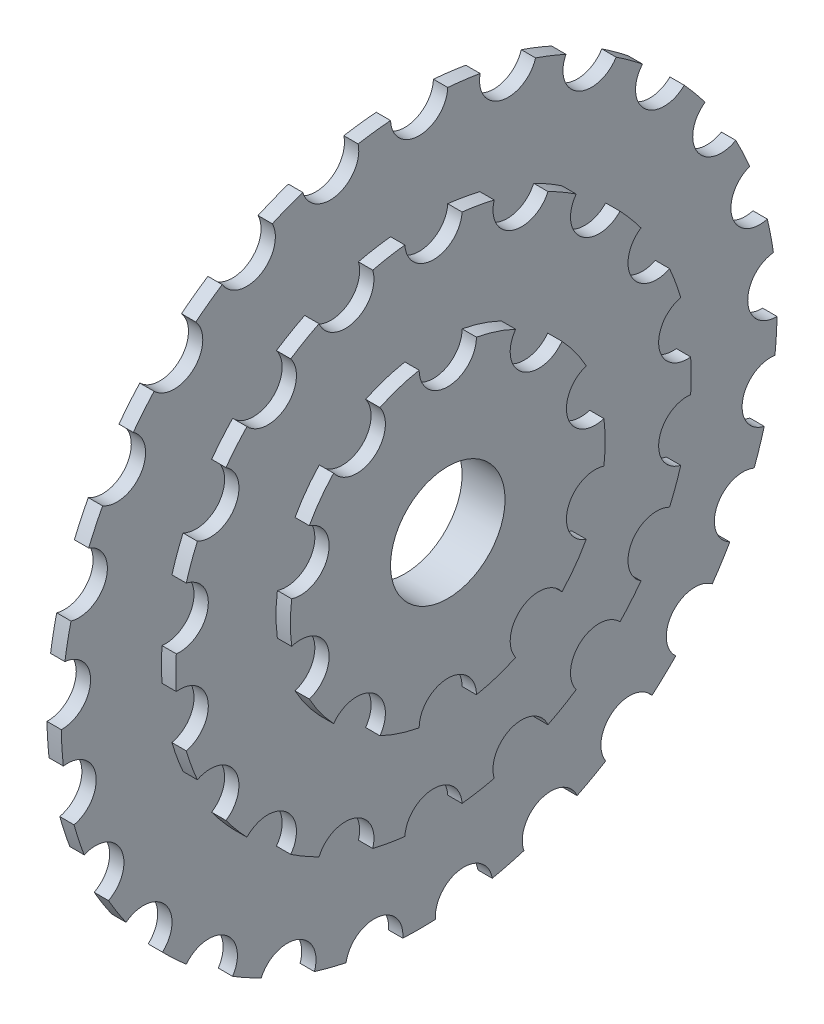
SolidWorks part; units mm, degrees
ref_plane "Front Plane" through (0, 0, 0) normal (0, 0, 1) x (1, 0, 0)
ref_plane "Top Plane" through (0, 0, 0) normal (0, 1, 0) x (1, 0, 0)
ref_plane "Right Plane" through (0, 0, 0) normal (1, 0, 0) x (0, 0, -1)
sketch "Sketch1" plane through (0, 0, 0) normal (1, 0, 0) x (0, 0, -1)
  circle A0 centre (0, 0) radius 338.5
  dimension "D1" = 677
sketch "Sketch2" plane through (0, 0, 0) normal (1, 0, 0) x (0, 0, -1)
  line L0 (-935.3702, 226.3146) -> (-163.5974, 226.3146) construction
sketch "Sketch3" plane through (0, 0, 0) normal (1, 0, 0) x (0, 0, -1)
  line L2 (-1063.2861, 71.897) -> (-1063.2861, -34.0827) construction
  arc A0 (-1068.2821, 62.3) -> (-1073.9404, 61.5852) centre (-1063.2861, 0) ccw
  arc A1 (-1068.2821, 62.3) -> (-1058.2901, 62.3) centre (-1063.2861, 62.5) ccw
  arc A2 (-1052.6317, 61.5852) -> (-1042.9537, 59.1003) centre (-1047.743, 60.5364) ccw
  arc A3 (-1037.6508, 57.0007) -> (-1028.8948, 52.1871) centre (-1033.1765, 54.7692) ccw
  arc A4 (-1024.2807, 48.8347) -> (-1016.9969, 41.9947) centre (-1020.5019, 45.5605) ccw
  arc A5 (-1013.3614, 37.6003) -> (-1008.0075, 29.1637) centre (-1010.5156, 33.4892) ccw
  arc A6 (-1005.5791, 24.0032) -> (-1002.4914, 14.5003) centre (-1003.845, 19.3136) ccw
  arc A7 (-1001.4227, 8.898) -> (-1000.7953, -1.0743) centre (-1000.9094, 3.9244) ccw
  arc A8 (-1001.1534, -6.7664) -> (-1003.0257, -16.5814) centre (-1001.8931, -11.7113) ccw
  arc A9 (-1004.7882, -22.0055) -> (-1009.0425, -31.0466) centre (-1006.7344, -26.6112) ccw
  arc A10 (-1012.0985, -35.862) -> (-1018.4677, -43.561) centre (-1015.129, -39.839) ccw
  arc A11 (-1022.6252, -47.4652) -> (-1030.7089, -53.3383) centre (-1026.5495, -50.5636) ccw
  arc A12 (-1035.7068, -56.0859) -> (-1044.9971, -59.7642) centre (-1040.2783, -58.111) ccw
  arc A13 (-1050.5212, -61.1826) -> (-1060.4344, -62.4349) centre (-1055.4527, -62.0072) ccw
  arc A14 (-1066.1377, -62.4349) -> (-1076.0509, -61.1826) centre (-1071.1194, -62.0072) ccw
  arc A15 (-1081.5751, -59.7642) -> (-1090.8654, -56.0859) centre (-1086.2939, -58.111) ccw
  arc A16 (-1095.8632, -53.3383) -> (-1103.9469, -47.4652) centre (-1100.0227, -50.5636) ccw
  arc A17 (-1108.1045, -43.561) -> (-1114.4736, -35.862) centre (-1111.4432, -39.839) ccw
  arc A18 (-1117.5296, -31.0466) -> (-1121.784, -22.0055) centre (-1119.8378, -26.6112) ccw
  arc A19 (-1123.5464, -16.5814) -> (-1125.4187, -6.7664) centre (-1124.679, -11.7113) ccw
  arc A20 (-1125.7768, -1.0743) -> (-1125.1494, 8.898) centre (-1125.6627, 3.9244) ccw
  arc A21 (-1124.0807, 14.5003) -> (-1120.993, 24.0032) centre (-1122.7271, 19.3136) ccw
  arc A22 (-1118.5647, 29.1637) -> (-1113.2107, 37.6003) centre (-1116.0566, 33.4892) ccw
  arc A23 (-1109.5753, 41.9947) -> (-1102.2914, 48.8347) centre (-1106.0703, 45.5605) ccw
  arc A24 (-1097.6774, 52.1871) -> (-1088.9213, 57.0007) centre (-1093.3957, 54.7692) ccw
  arc A25 (-1083.6185, 59.1003) -> (-1073.9404, 61.5852) centre (-1078.8292, 60.5364) ccw
  arc A26 (-1083.6185, 59.1003) -> (-1088.9213, 57.0007) centre (-1063.2861, 0) ccw
  arc A27 (-1097.6774, 52.1871) -> (-1102.2914, 48.8347) centre (-1063.2861, 0) ccw
  arc A28 (-1109.5753, 41.9947) -> (-1113.2107, 37.6003) centre (-1063.2861, 0) ccw
  arc A29 (-1118.5647, 29.1637) -> (-1120.993, 24.0032) centre (-1063.2861, 0) ccw
  arc A30 (-1124.0807, 14.5003) -> (-1125.1494, 8.898) centre (-1063.2861, 0) ccw
  arc A31 (-1125.7768, -1.0743) -> (-1125.4187, -6.7664) centre (-1063.2861, 0) ccw
  arc A32 (-1123.5464, -16.5814) -> (-1121.784, -22.0055) centre (-1063.2861, 0) ccw
  arc A33 (-1117.5296, -31.0466) -> (-1114.4736, -35.862) centre (-1063.2861, 0) ccw
  arc A34 (-1108.1045, -43.561) -> (-1103.9469, -47.4652) centre (-1063.2861, 0) ccw
  arc A35 (-1095.8632, -53.3383) -> (-1090.8654, -56.0859) centre (-1063.2861, 0) ccw
  arc A36 (-1081.5751, -59.7642) -> (-1076.0509, -61.1826) centre (-1063.2861, 0) ccw
  arc A37 (-1066.1377, -62.4349) -> (-1060.4344, -62.4349) centre (-1063.2861, 0) ccw
  arc A38 (-1050.5212, -61.1826) -> (-1044.9971, -59.7642) centre (-1063.2861, 0) ccw
  arc A39 (-1035.7068, -56.0859) -> (-1030.7089, -53.3383) centre (-1063.2861, 0) ccw
  arc A40 (-1022.6252, -47.4652) -> (-1018.4677, -43.561) centre (-1063.2861, 0) ccw
  arc A41 (-1012.0985, -35.862) -> (-1009.0425, -31.0466) centre (-1063.2861, 0) ccw
  arc A42 (-1004.7882, -22.0055) -> (-1003.0257, -16.5814) centre (-1063.2861, 0) ccw
  arc A43 (-1001.1534, -6.7664) -> (-1000.7953, -1.0743) centre (-1063.2861, 0) ccw
  arc A44 (-1001.4227, 8.898) -> (-1002.4914, 14.5003) centre (-1063.2861, 0) ccw
  arc A45 (-1005.5791, 24.0032) -> (-1008.0075, 29.1637) centre (-1063.2861, 0) ccw
  arc A46 (-1013.3614, 37.6003) -> (-1016.9969, 41.9947) centre (-1063.2861, 0) ccw
  arc A47 (-1024.2807, 48.8347) -> (-1028.8948, 52.1871) centre (-1063.2861, 0) ccw
  arc A48 (-1037.6508, 57.0007) -> (-1042.9537, 59.1003) centre (-1063.2861, 0) ccw
  arc A49 (-1052.6317, 61.5852) -> (-1058.2901, 62.3) centre (-1063.2861, 0) ccw
  point P81 (-1063.2861, 0)
  dimension "D1" = 125
  dimension "D3" = 10
  dimension "D2" = 25
extrude "Boss-Extrude1" add sketch "Sketch3" along normal blind 2.5
sketch "Sketch4" plane through (2.5, 0, 0) normal (1, 0, 0) x (0, 0, -1)
  line L2 (-1063.2861, 49.1439) -> (-1063.2861, -23.1666) construction
  arc A0 (-1068.2784, 44.7222) -> (-1073.8908, 43.7326) centre (-1063.2861, 0) ccw
  arc A1 (-1068.2784, 44.7222) -> (-1058.2938, 44.7222) centre (-1063.2861, 45) ccw
  arc A2 (-1052.6814, 43.7326) -> (-1043.299, 40.3177) centre (-1047.8952, 42.2862) ccw
  arc A3 (-1038.3635, 37.4682) -> (-1030.7149, 31.0502) centre (-1034.3606, 34.472) ccw
  arc A4 (-1027.0516, 26.6846) -> (-1022.0594, 18.0377) centre (-1024.3149, 22.5) ccw
  arc A5 (-1020.1102, 12.6824) -> (-1018.3764, 2.8495) centre (-1018.9697, 7.8142) ccw
  arc A6 (-1018.3764, -2.8495) -> (-1020.1102, -12.6824) centre (-1018.9697, -7.8142) ccw
  arc A7 (-1022.0594, -18.0377) -> (-1027.0516, -26.6846) centre (-1024.3149, -22.5) ccw
  arc A8 (-1030.7149, -31.0502) -> (-1038.3635, -37.4682) centre (-1034.3606, -34.472) ccw
  arc A9 (-1043.299, -40.3177) -> (-1052.6814, -43.7326) centre (-1047.8952, -42.2862) ccw
  arc A10 (-1058.2938, -44.7222) -> (-1068.2784, -44.7222) centre (-1063.2861, -45) ccw
  arc A11 (-1073.8908, -43.7326) -> (-1083.2732, -40.3177) centre (-1078.677, -42.2862) ccw
  arc A12 (-1088.2087, -37.4682) -> (-1095.8573, -31.0502) centre (-1092.2115, -34.472) ccw
  arc A13 (-1099.5205, -26.6846) -> (-1104.5128, -18.0377) centre (-1102.2572, -22.5) ccw
  arc A14 (-1106.462, -12.6824) -> (-1108.1958, -2.8495) centre (-1107.6024, -7.8142) ccw
  arc A15 (-1108.1958, 2.8495) -> (-1106.462, 12.6824) centre (-1107.6024, 7.8142) ccw
  arc A16 (-1104.5128, 18.0377) -> (-1099.5205, 26.6846) centre (-1102.2572, 22.5) ccw
  arc A17 (-1095.8573, 31.0502) -> (-1088.2087, 37.4682) centre (-1092.2115, 34.472) ccw
  arc A18 (-1083.2732, 40.3177) -> (-1073.8908, 43.7326) centre (-1078.677, 42.2862) ccw
  arc A19 (-1083.2732, 40.3177) -> (-1088.2087, 37.4682) centre (-1063.2861, 0) ccw
  arc A20 (-1095.8573, 31.0502) -> (-1099.5205, 26.6846) centre (-1063.2861, 0) ccw
  arc A21 (-1104.5128, 18.0377) -> (-1106.462, 12.6824) centre (-1063.2861, 0) ccw
  arc A22 (-1108.1958, 2.8495) -> (-1108.1958, -2.8495) centre (-1063.2861, 0) ccw
  arc A23 (-1106.462, -12.6824) -> (-1104.5128, -18.0377) centre (-1063.2861, 0) ccw
  arc A24 (-1099.5205, -26.6846) -> (-1095.8573, -31.0502) centre (-1063.2861, 0) ccw
  arc A25 (-1088.2087, -37.4682) -> (-1083.2732, -40.3177) centre (-1063.2861, 0) ccw
  arc A26 (-1073.8908, -43.7326) -> (-1068.2784, -44.7222) centre (-1063.2861, 0) ccw
  arc A27 (-1058.2938, -44.7222) -> (-1052.6814, -43.7326) centre (-1063.2861, 0) ccw
  arc A28 (-1043.299, -40.3177) -> (-1038.3635, -37.4682) centre (-1063.2861, 0) ccw
  arc A29 (-1030.7149, -31.0502) -> (-1027.0516, -26.6846) centre (-1063.2861, 0) ccw
  arc A30 (-1022.0594, -18.0377) -> (-1020.1102, -12.6824) centre (-1063.2861, 0) ccw
  arc A31 (-1018.3764, -2.8495) -> (-1018.3764, 2.8495) centre (-1063.2861, 0) ccw
  arc A32 (-1020.1102, 12.6824) -> (-1022.0594, 18.0377) centre (-1063.2861, 0) ccw
  arc A33 (-1027.0516, 26.6846) -> (-1030.7149, 31.0502) centre (-1063.2861, 0) ccw
  arc A34 (-1038.3635, 37.4682) -> (-1043.299, 40.3177) centre (-1063.2861, 0) ccw
  arc A35 (-1052.6814, 43.7326) -> (-1058.2938, 44.7222) centre (-1063.2861, 0) ccw
  point P62 (-1063.2861, 0)
  dimension "D1" = 90
  dimension "D3" = 10
  dimension "D2" = 18
extrude "Boss-Extrude2" add sketch "Sketch4" along normal blind 2.5
sketch "Sketch5" plane through (5, 0, 0) normal (1, 0, 0) x (0, 0, -1)
  line L2 (-1063.2861, 30.8125) -> (-1063.2861, -13.6373) construction
  arc A0 (-1068.2861, 27.0416) -> (-1075.1357, 24.8161) centre (-1063.2861, 0) ccw
  arc A1 (-1068.2861, 27.0416) -> (-1058.2861, 27.0416) centre (-1063.2861, 27.0416) ccw
  arc A2 (-1051.4365, 24.8161) -> (-1043.3463, 18.9382) centre (-1047.3914, 21.8771) ccw
  arc A3 (-1039.113, 13.1116) -> (-1036.0229, 3.601) centre (-1037.568, 8.3563) ccw
  arc A4 (-1036.0229, -3.601) -> (-1039.113, -13.1116) centre (-1037.568, -8.3563) ccw
  arc A5 (-1043.3463, -18.9382) -> (-1051.4365, -24.8161) centre (-1047.3914, -21.8771) ccw
  arc A6 (-1058.2861, -27.0416) -> (-1068.2861, -27.0416) centre (-1063.2861, -27.0416) ccw
  arc A7 (-1075.1357, -24.8161) -> (-1083.2258, -18.9382) centre (-1079.1807, -21.8771) ccw
  arc A8 (-1087.4591, -13.1116) -> (-1090.5493, -3.601) centre (-1089.0042, -8.3563) ccw
  arc A9 (-1090.5493, 3.601) -> (-1087.4591, 13.1116) centre (-1089.0042, 8.3563) ccw
  arc A10 (-1083.2258, 18.9382) -> (-1075.1357, 24.8161) centre (-1079.1807, 21.8771) ccw
  arc A11 (-1083.2258, 18.9382) -> (-1087.4591, 13.1116) centre (-1063.2861, 0) ccw
  arc A12 (-1090.5493, 3.601) -> (-1090.5493, -3.601) centre (-1063.2861, 0) ccw
  arc A13 (-1087.4591, -13.1116) -> (-1083.2258, -18.9382) centre (-1063.2861, 0) ccw
  arc A14 (-1075.1357, -24.8161) -> (-1068.2861, -27.0416) centre (-1063.2861, 0) ccw
  arc A15 (-1058.2861, -27.0416) -> (-1051.4365, -24.8161) centre (-1063.2861, 0) ccw
  arc A16 (-1043.3463, -18.9382) -> (-1039.113, -13.1116) centre (-1063.2861, 0) ccw
  arc A17 (-1036.0229, -3.601) -> (-1036.0229, 3.601) centre (-1063.2861, 0) ccw
  arc A18 (-1039.113, 13.1116) -> (-1043.3463, 18.9382) centre (-1063.2861, 0) ccw
  arc A19 (-1051.4365, 24.8161) -> (-1058.2861, 27.0416) centre (-1063.2861, 0) ccw
  point P37 (-1063.2861, 0)
  dimension "D1" = 55
  dimension "D2" = 10
  dimension "D3" = 10
extrude "Boss-Extrude3" add sketch "Sketch5" along normal blind 2.5
sketch "Sketch6" plane through (0, 0, 0) normal (1, 0, 0) x (0, 0, -1)
  circle A0 centre (-1063.2861, 0) radius 10
  dimension "D1" = 20
extrude "Cut-Extrude1" cut sketch "Sketch6" along normal through all
ref_plane "Plane1" through (2.5, 0, 0) normal (1, 0, 0) x (0, 0, -1)
ref_plane "Plane2" through (5, 0, 0) normal (1, 0, 0) x (0, 0, -1)
